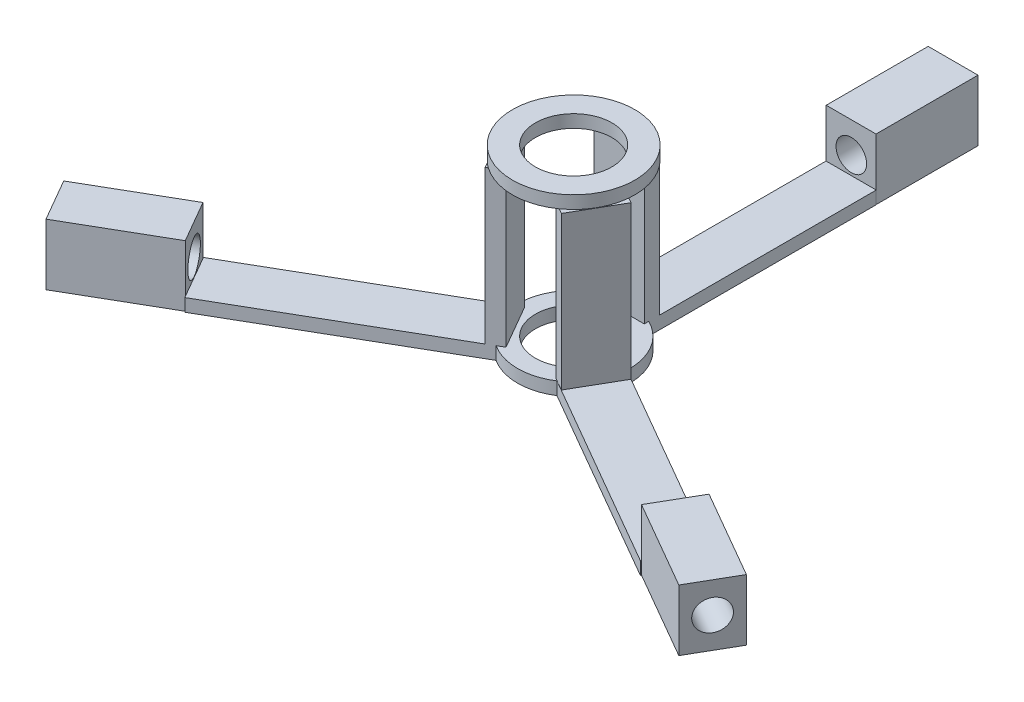
SolidWorks part; units mm, degrees
ref_plane "Front Plane" through (0, 0, 0) normal (0, 0, 1) x (1, 0, 0)
ref_plane "Top Plane" through (0, 0, 0) normal (0, 1, 0) x (1, 0, 0)
ref_plane "Right Plane" through (0, 0, 0) normal (1, 0, 0) x (0, 0, -1)
sketch "Sketch1" plane through (0, 0, 0) normal (0, 1, 0) x (1, 0, 0)
  circle A0 centre (0, 0) radius 5.5
extrude "Boss-Extrude1" add sketch "Sketch1" along normal blind 1.25
sketch "Sketch2" plane through (0, 1.25, 0) normal (0, 1, 0) x (1, 0, 0)
  circle A0 centre (0, 0) radius 3.75
extrude "Cut-Extrude1" cut sketch "Sketch2" against normal blind 1.25
sketch "Sketch3" plane through (0, 1.25, 0) normal (0, 1, 0) x (1, 0, 0)
  line L0 (0, 0) -> (0, 5.5)
  line L1 (0, 5.5) -> (0, 3.7499)
  line L2 (0, 0) -> (-4.7631, -2.75)
  line L3 (0, 0) -> (4.7631, -2.75)
  line L4 (-4.7631, -2.75) -> (-22.0836, -12.75)
  line L5 (-4.7631, -2.75) -> (-3.2476, -1.875)
  line L6 (-3.2476, -1.875) -> (-1.9976, -4.0401)
  line L7 (-24.8427, -11.4713) -> (-4.4911, 0.2787)
  line L8 (-24.8427, -11.4713) -> (-22.3492, -15.7901)
  line L9 (-4.4911, 0.2787) -> (-1.9976, -4.0401)
  line L10 (-22.3492, -15.7901) -> (-1.9976, -4.0401)
  line L11 (-24.8427, -11.4713) -> (-1.9976, -4.0401) construction
  line L12 (-4.4911, 0.2787) -> (-22.3492, -15.7901) construction
  line L13 (4.7631, -2.75) -> (3.2476, -1.875)
  line L14 (3.2476, -1.875) -> (4.4976, 0.2901)
  line L15 (4.7631, -2.75) -> (22.0836, -12.75)
  line L16 (22.3433, -15.8003) -> (1.9917, -4.0503)
  line L17 (22.3433, -15.8003) -> (24.8492, -11.4599)
  line L18 (1.9917, -4.0503) -> (4.4976, 0.2901)
  line L19 (24.8492, -11.4599) -> (4.4976, 0.2901)
  line L20 (22.3433, -15.8003) -> (4.4976, 0.2901) construction
  line L21 (1.9917, -4.0503) -> (24.8492, -11.4599) construction
  line L22 (0, 5.5) -> (0, 25.5)
  line L23 (0, 3.7499) -> (-2.5, 3.7499)
  line L24 (2.4263, 27.2501) -> (2.4263, 3.7499)
  line L25 (2.4263, 27.2501) -> (-2.5, 27.2501)
  line L26 (2.4263, 3.7499) -> (-2.5, 3.7499)
  line L27 (-2.5, 27.2501) -> (-2.5, 3.7499)
  line L28 (2.4263, 27.2501) -> (-2.5, 3.7499) construction
  line L29 (2.4263, 3.7499) -> (-2.5, 27.2501) construction
  circle A0 centre (0, 0) radius 5.5 construction
  circle A1 centre (0, 0) radius 3.75 construction
  point P15 (-13.4201, -7.7557)
  point P22 (13.4204, -7.7551)
  point P28 (-0.0369, 15.5)
  dimension "D1" = 5.5
extrude "Boss-Extrude6" add sketch "Sketch3" against normal blind 1.25
sketch "Sketch6" plane through (0, 1.25, 0) normal (0, 1, 0) x (1, 0, 0)
  line L0 (-0.0369, 27.2501) -> (-0.0369, 5.2501)
  line L1 (2.4263, 27.2501) -> (-2.5, 27.2501) construction
  line L2 (-23.5959, -13.6307) -> (-4.2731, -2.4746)
  line L3 (-24.8427, -11.4713) -> (-22.3492, -15.7901) construction
  line L4 (23.5962, -13.6301) -> (4.5745, -2.6411)
  line L5 (22.3433, -15.8003) -> (24.8492, -11.4599) construction
  line L6 (-4.2731, -2.4746) -> (-3.0263, -4.634)
  line L7 (-2.5, 6.0001) -> (2.4263, 6.0001)
  line L8 (-2.5, 6.0001) -> (-2.5, 4.5001)
  line L9 (-2.5, 4.5001) -> (2.4263, 4.5001)
  line L10 (2.4263, 6.0001) -> (2.4263, 4.5001)
  line L11 (-2.5, 6.0001) -> (2.4263, 4.5001) construction
  line L12 (-2.5, 4.5001) -> (2.4263, 6.0001) construction
  line L13 (-22.3492, -15.7901) -> (-2.9926, -4.6146) construction
  line L14 (-6.1693, -0.6902) -> (-3.6758, -5.009)
  line L15 (-6.1693, -0.6902) -> (-4.8703, 0.0598)
  line L16 (-3.6758, -5.009) -> (-2.3768, -4.259)
  line L17 (-4.8703, 0.0598) -> (-2.3768, -4.259)
  line L18 (-6.1693, -0.6902) -> (-2.3768, -4.259) construction
  line L19 (-3.6758, -5.009) -> (-4.8703, 0.0598) construction
  line L20 (4.5745, -2.6411) -> (5.8245, -0.476)
  line L21 (24.8492, -11.4599) -> (5.4926, -0.2844) construction
  line L22 (3.974, -5.1811) -> (6.474, -0.851)
  line L23 (3.974, -5.1811) -> (2.675, -4.4311)
  line L24 (6.474, -0.851) -> (5.175, -0.101)
  line L25 (2.675, -4.4311) -> (5.175, -0.101)
  line L26 (3.974, -5.1811) -> (5.175, -0.101) construction
  line L27 (6.474, -0.851) -> (2.675, -4.4311) construction
extrude "Boss-Extrude7" add sketch "Sketch6" along normal blind 15 contours L24 L25 L23 L22 | L10 L9 L8 L7 | L16 L17 L15 L14
sketch "Sketch8" plane through (0, 16.25, 0) normal (0, 1, 0) x (1, 0, 0)
  circle A0 centre (0, 0) radius 6
extrude "Boss-Extrude8" add sketch "Sketch8" along normal blind 1.25
sketch "Sketch9" plane through (0, 17.5, 0) normal (0, 1, 0) x (1, 0, 0)
  circle A0 centre (0, 0) radius 3.75
extrude "Cut-Extrude3" cut sketch "Sketch9" against normal blind 1.25
sketch "Sketch10" plane through (0, 1.25, 0) normal (0, 1, 0) x (1, 0, 0)
  line L0 (-23.5959, -13.6307) -> (-32.2562, -18.6307)
  line L1 (-24.8427, -11.4713) -> (-22.3492, -15.7901) construction
  line L2 (-31.0692, -20.6865) -> (-22.409, -15.6865)
  line L3 (-31.0692, -20.6865) -> (-33.4431, -16.5748)
  line L4 (-22.409, -15.6865) -> (-24.7829, -11.5748)
  line L5 (-33.4431, -16.5748) -> (-24.7829, -11.5748)
  line L6 (-31.0692, -20.6865) -> (-24.7829, -11.5748) construction
  line L7 (-22.409, -15.6865) -> (-33.4431, -16.5748) construction
  line L8 (-0.0369, 27.2501) -> (-0.0369, 37.2501)
  line L9 (2.4263, 27.2501) -> (-2.5, 27.2501) construction
  line L10 (-2.4812, 37.2501) -> (-2.4812, 27.2501)
  line L11 (-2.4812, 37.2501) -> (2.4075, 37.2501)
  line L12 (-2.4812, 27.2501) -> (2.4075, 27.2501)
  line L13 (2.4075, 37.2501) -> (2.4075, 27.2501)
  line L14 (-2.4812, 37.2501) -> (2.4075, 27.2501) construction
  line L15 (-2.4812, 27.2501) -> (2.4075, 37.2501) construction
  line L16 (23.5962, -13.6301) -> (32.2565, -18.6301)
  line L17 (22.3433, -15.8003) -> (24.8492, -11.4599) construction
  line L18 (31.044, -20.7302) -> (22.3838, -15.7302)
  line L19 (31.044, -20.7302) -> (33.469, -16.53)
  line L20 (22.3838, -15.7302) -> (24.8087, -11.53)
  line L21 (33.469, -16.53) -> (24.8087, -11.53)
  line L22 (31.044, -20.7302) -> (24.8087, -11.53) construction
  line L23 (22.3838, -15.7302) -> (33.469, -16.53) construction
  point P5 (-27.9261, -16.1307)
  point P14 (-0.0369, 32.2501)
  point P23 (27.9264, -16.1301)
extrude "Boss-Extrude9" add sketch "Sketch10" against normal blind 1.25 and the other way blind 4.75 contours L5 L3 L0 | L19 L21 L20 L18 | L11 L13 L12 L10
sketch "Sketch11" plane through (-32.2594, 0, 18.625) normal (-0.866, 0, 0.5) x (0.5, 0, 0.866)
  line L0 (0.0065, 6) -> (0.0065, 0)
  line L1 (2.3804, 6) -> (-2.3674, 6) construction
  line L2 (2.3804, 0) -> (-2.3674, 0) construction
  circle A0 centre (0.0065, 3) radius 1.6691
extrude "Cut-Extrude4" cut sketch "Sketch11" against normal blind 10 contours A0
sketch "Sketch12" plane through (0, 0, -37.2501) normal (0, 0, -1) x (-1, 0, 0)
  line L0 (0.0369, 6) -> (0, 0)
  line L1 (2.4812, 6) -> (-2.4075, 6) construction
  circle A0 centre (0.0184, 3) radius 1.5
extrude "Cut-Extrude5" cut sketch "Sketch12" against normal blind 10 contours A0
sketch "Sketch13" plane through (32.2594, 0, 18.625) normal (0.866, 0, 0.5) x (0.5, 0, -0.866)
  line L0 (-0.0059, 6) -> (-0.0059, 0)
  line L1 (-2.4308, 6) -> (2.4191, 6) construction
  line L2 (-2.4308, 0) -> (2.4191, 0) construction
  circle A0 centre (-0.0059, 3) radius 1.5
extrude "Cut-Extrude6" cut sketch "Sketch13" against normal blind 10 contours A0
